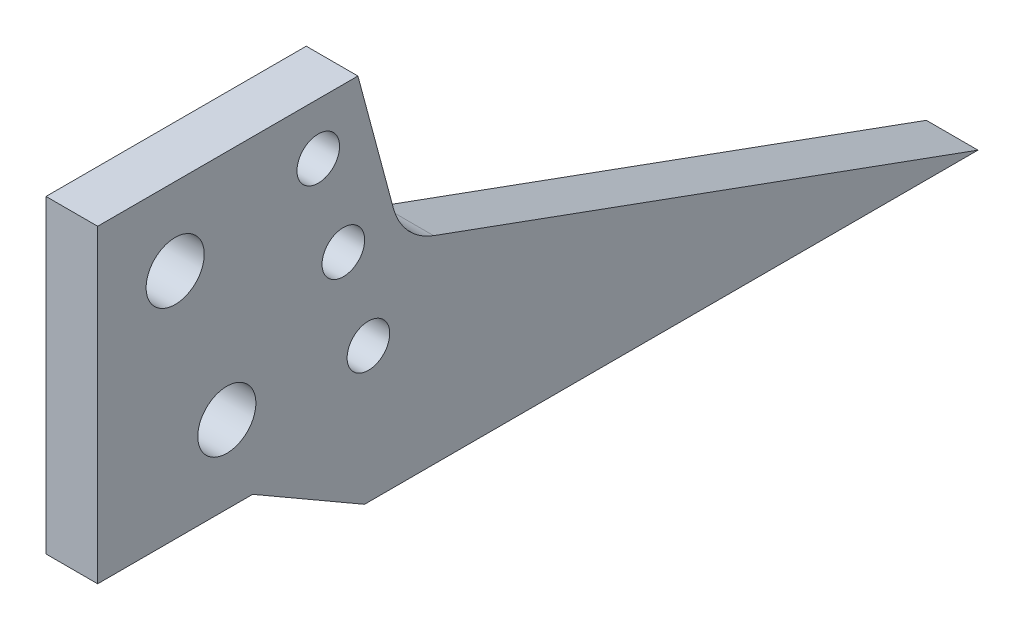
SolidWorks part; units mm, degrees
material "AISI 4340 Aço recozido"
ref_plane "Plano frontal" through (0, 0, 0) normal (0, 0, 1) x (1, 0, 0)
ref_plane "Plano superior" through (0, 0, 0) normal (0, 1, 0) x (1, 0, 0)
ref_plane "Plano direito" through (0, 0, 0) normal (1, 0, 0) x (0, 0, -1)
sketch "Esboço1" plane through (0, 0, 0) normal (1, 0, 0) x (0, 0, -1)
  line L1 (28, 74) -> (39.1299, 32.4627)
  line L3 (33.3205, 0) -> (128.3205, 0)
  line L4 (28, 74) -> (0, 74)
  line L8 (128.3205, 0) -> (39.1299, 32.4627)
  line L10 (16, 10) -> (0, 10)
  line L11 (0, 10) -> (0, 74)
  line L12 (39.1299, 32.4627) -> (0, 32.4627) construction
  line L15 (33.3205, 0) -> (16, 10)
  dimension "D1" = 10
  dimension "D2" = 210
  dimension "D3" = 20
  dimension "D4" = 16
  dimension "D5" = 64
  dimension "D6" = 75
  dimension "D7" = 28
  dimension "D8" = 95
extrude "Ressalto-extrusão1" add sketch "Esboço1" along normal blind 8
sketch "Esboço2" plane through (8, 0, 0) normal (1, 0, 0) x (0, 0, -1)
  line L0 (39.1299, 32.4627) -> (28, 74) construction
  line L1 (0, 74) -> (32.3, 74)
  line L2 (0, 74) -> (0, 57.9522)
  line L3 (0, 57.9522) -> (32.3, 57.9522)
  line L4 (32.3, 74) -> (32.3, 57.9522)
  dimension "D1" = 32.3
extrude "Corte-extrusão1" cut sketch "Esboço2" against normal through all
sketch "Esboço3" plane through (8, 0, 0) normal (1, 0, 0) x (0, 0, -1)
  line L0 (0, 10) -> (16, 10) construction
  line L1 (0, 57.9522) -> (-8, 57.9522)
  line L2 (0, 57.9522) -> (0, 10)
  line L3 (0, 10) -> (-8, 10)
  line L4 (-8, 57.9522) -> (-8, 10)
  dimension "D1" = 8
extrude "Ressalto-extrusão2" add sketch "Esboço3" against normal up to surface (8 mm away) up to face at (0, 24.0524, -35.5816)
hole_wizard "Furo com folga de M81" positions "Esboço4" profile "Esboço5" hole size "M8" standard "ISO" end condition through all
sketch "Esboço4" plane through (0, 0, 0) normal (-1, 0, 0) x (0, 0, 1)
  line L0 (8, 57.9522) -> (8, 10) construction
  line L1 (8, 57.9522) -> (-32.3, 57.9522) construction
  line L2 (8, 10) -> (-16, 10) construction
  point P1 (-4, 45.9522)
  point P3 (-12, 22)
  dimension "D1" = 12
  dimension "D2" = 12
  dimension "D3" = 12
  dimension "D4" = 4
sketch "Esboço5" plane through (0, 45.9522, -4) normal (0, 1, 0) x (0, 0, 1)
  line L0 (0, 0) -> (0, 8)
  line L1 (0, 8) -> (4.5, 8)
  line L2 (4.5, 8) -> (4.5, 0)
  line L5 (4.5, 0) -> (0, 0)
  line L11 (0, -6.35) -> (0, 107.95) construction
  dimension "Thru Hole Dia." = 9
  dimension "Thru Hole Depth" = 8
hole_wizard "Furo com folga de M61" positions "Esboço6" profile "Esboço7" hole size "M6" standard "ISO" end condition through all
sketch "Esboço6" plane through (8, 0, 0) normal (1, 0, 0) x (0, 0, -1)
  line L0 (26.1614, 49.9522) -> (33.926, 20.9744) construction
  line L3 (-8, 57.9522) -> (-8, 10) construction
  line L6 (39.1299, 32.4627) -> (32.3, 57.9522) construction
  line L7 (-8, 57.9522) -> (32.3, 57.9522) construction
  point P0 (26.1614, 49.9522)
  point P2 (30.0437, 35.4633)
  point P4 (33.926, 20.9744)
  dimension "D1" = 8
  dimension "D2" = 15
  dimension "D3" = 15
  dimension "D4" = 30
  dimension "D5" = 8
sketch "Esboço7" plane through (8, 49.9522, -26.1614) normal (0, 1, 0) x (0, 0, -1)
  line L0 (0, 0) -> (0, 8)
  line L1 (0, 8) -> (3.3, 8)
  line L2 (3.3, 8) -> (3.3, 0)
  line L5 (3.3, 0) -> (0, 0)
  line L11 (0, -6.35) -> (0, 107.95) construction
  dimension "Thru Hole Dia." = 6.6
  dimension "Thru Hole Depth" = 8
sketch "Esboço8" plane through (8, 0, 0) normal (1, 0, 0) x (0, 0, -1)
  line L0 (128.3205, 0) -> (68.3205, 0)
  line L1 (33.3205, 0) -> (128.3205, 0) construction
  line L2 (68.3205, 0) -> (68.3205, -2.0952)
  line L3 (68.3205, -2.0952) -> (128.3205, 0)
  dimension "D1" = 60
  dimension "D2" = 2
extrude "Ressalto-extrusão3" [suppressed] add sketch "Esboço8" against normal blind 8
fillet "Filete1" radius 10 1 edges at (4, 32.4627, -39.1299)
fillet "Filete2" [suppressed] radius 10
